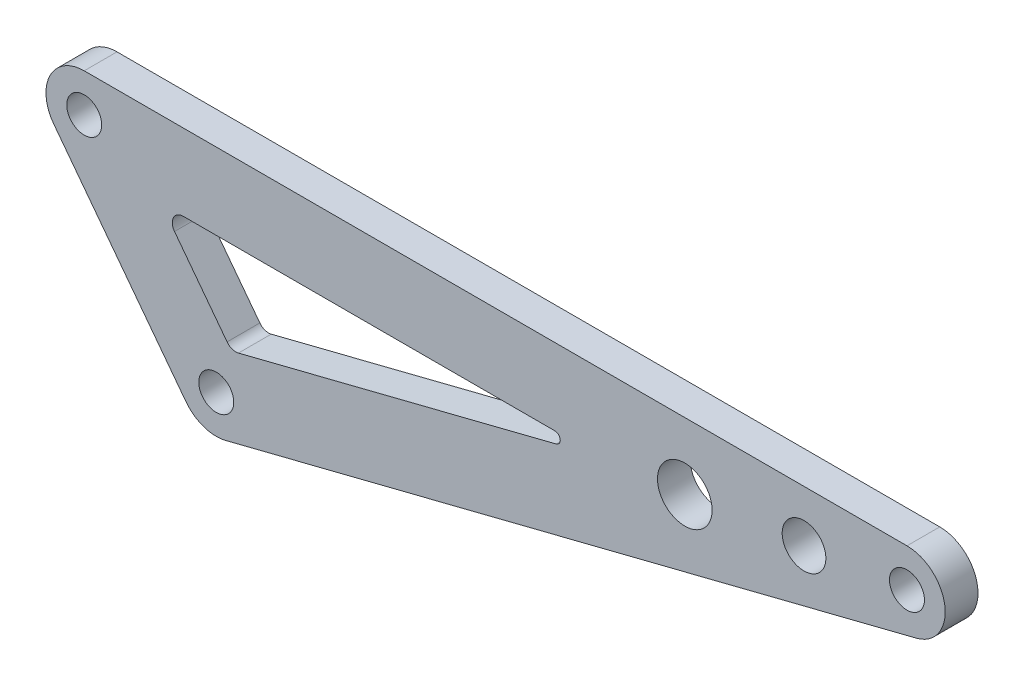
SolidWorks part; units mm, degrees
material "5052-O"
ref_plane "正面" through (0, 0, 0) normal (0, 0, 1) x (1, 0, 0)
ref_plane "平面" through (0, 0, 0) normal (0, 1, 0) x (1, 0, 0)
ref_plane "右側面" through (0, 0, 0) normal (1, 0, 0) x (0, 0, -1)
sketch "ｽｹｯﾁ1" plane through (0, 0, 0) normal (0, 0, 1) x (1, 0, 0)
  line L0 (-47.8081, -36.2545) -> (0, 0) construction
  line L1 (0, 0) -> (27.493, -36.2545) construction
  line L2 (27.493, -36.2545) -> (-47.8081, -36.2545) construction
  line L3 (-68.9608, 0) -> (77.208, 0) construction
  line L4 (0, 43.1663) -> (0, -38.955) construction
  line L5 (-47.8081, -32.7545) -> (27.493, -32.7545)
  line L6 (-40.7614, -39.7545) -> (-0.7095, -39.7545)
  line L7 (-47.8081, -36.2545) -> (-35.7233, -52.1905) construction
  line L8 (-35.7233, -52.1905) -> (27.493, -36.2545) construction
  line L9 (-40.7614, -39.7545) -> (-34.3336, -48.2307)
  line L10 (-34.3336, -48.2307) -> (-0.7095, -39.7545)
  line L11 (-50.5969, -38.3693) -> (-38.5121, -54.3053)
  line L12 (-34.8677, -55.5843) -> (28.3485, -39.6483)
  circle A2 centre (-47.8081, -36.2545) radius 1.6
  circle A3 centre (27.493, -36.2545) radius 1.6
  arc A4 (-47.8081, -32.7545) -> (-50.5969, -38.3693) centre (-47.8081, -36.2545) ccw
  arc A5 (27.493, -32.7545) -> (28.3485, -39.6483) centre (27.493, -36.2545) cw
  arc A6 (-38.5121, -54.3053) -> (-34.8677, -55.5843) centre (-35.7233, -52.1905) ccw
  circle A7 centre (-35.7233, -52.1905) radius 1.6
  dimension "D4" = 3.2
  dimension "D5" = 3.5
  dimension "D11" = 3.5
  dimension "D1" = 60
  dimension "D2" = 45.5
  dimension "D3" = 3.5
  dimension "D6" = 20
  dimension "D7" = 7
  dimension "D8" = 3.5
  dimension "D9" = 7
  dimension "D10" = 7
extrude "ﾎﾞｽ - 押し出し1" add sketch "ｽｹｯﾁ1" along normal blind 3
fillet "ﾌｨﾚｯﾄ1" radius 0.5 1 edges at (-0.7095, -39.7545, 1.5)
fillet "ﾌｨﾚｯﾄ2" radius 1 2 edges at (-34.3336, -48.2307, 1.5) (-40.7614, -39.7545, 1.5)
sketch "ｽｹｯﾁ2" plane through (0, 0, 3) normal (0, 0, 1) x (1, 0, 0)
  line L0 (27.493, -36.2545) -> (-37.1391, -44.5311) construction
  line L1 (-39.5448, -41.3587) -> (-34.7333, -47.7035) construction
  circle A1 centre (7.159, -38.8584) radius 2.5
  circle A2 centre (18.0699, -37.4612) radius 2
  dimension "D2" = 5
  dimension "D3" = 4
  dimension "D4" = 9.5
  dimension "D5" = 11
extrude "ｶｯﾄ - 押し出し1" cut sketch "ｽｹｯﾁ2" against normal through all
